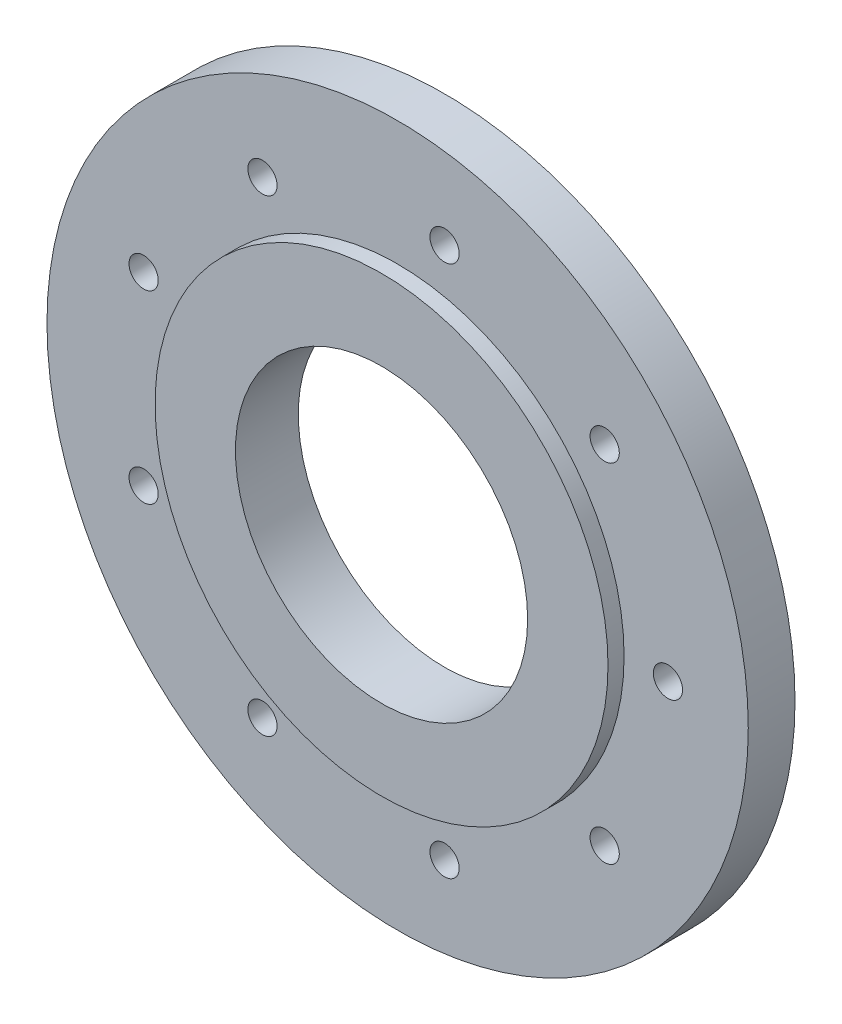
SolidWorks part; units mm, degrees
ref_plane "Front Plane" through (0, 0, 0) normal (0, 0, 1) x (1, 0, 0)
ref_plane "Top Plane" through (0, 0, 0) normal (0, 1, 0) x (1, 0, 0)
ref_plane "Right Plane" through (0, 0, 0) normal (1, 0, 0) x (0, 0, -1)
sketch "Sketch1" plane through (0, 0, 0) normal (0, 0, 1) x (1, 0, 0)
  circle A0 centre (0, 0) radius 120
  dimension "D1" = 240
extrude "Boss-Extrude1" add sketch "Sketch1" along normal blind 21.5
sketch "Sketch2" plane through (0, 0, 21.5) normal (0, 0, 1) x (1, 0, 0)
  circle A0 centre (0, 0) radius 77.5
  dimension "D1" = 155
extrude "Cut-Extrude1" cut sketch "Sketch2" against normal blind 5.5 flip side to cut
sketch "Sketch3" plane through (0, 0, 16) normal (0, 0, 1) x (1, 0, 0)
  circle A0 centre (0, 0) radius 92.5 construction
  circle A1 centre (92.5, 0) radius 5
  dimension "D1" = 185
  dimension "D2" = 10
extrude "Cut-Extrude2" cut sketch "Sketch3" against normal through all
pattern_circular "CirPattern1" count 9 over 360 about axis through (0, 0, 0) along (0, 0, 1) of "Cut-Extrude2"
sketch "Sketch4" plane through (0, 0, 21.5) normal (0, 0, 1) x (1, 0, 0)
  circle A0 centre (0, 0) radius 50
  dimension "D1" = 100
extrude "Cut-Extrude3" cut sketch "Sketch4" against normal through all
